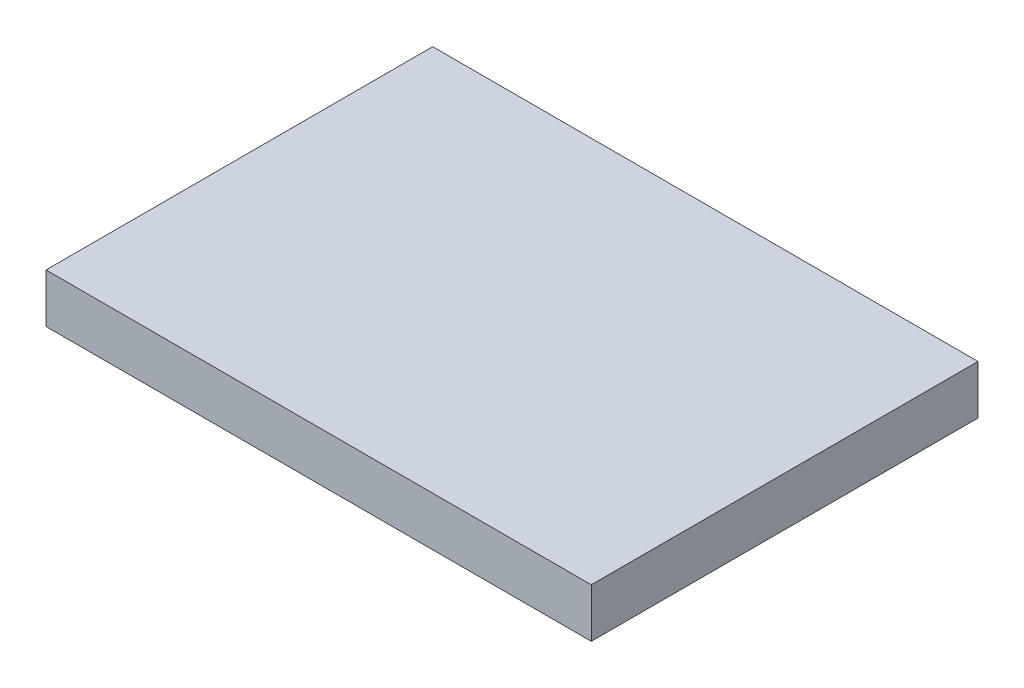
SolidWorks part; units mm, degrees
material "Plain Carbon Steel"
ref_plane "Front Plane" through (0, 0, 0) normal (0, 0, 1) x (1, 0, 0)
ref_plane "Top Plane" through (0, 0, 0) normal (0, 1, 0) x (1, 0, 0)
ref_plane "Right Plane" through (0, 0, 0) normal (1, 0, 0) x (0, 0, -1)
sketch "Sketch1" plane through (0, 0, 0) normal (0, 0, 1) x (1, 0, 0)
  line L1 (-39.6474, -7.3068) -> (2.6526, -7.3068)
  line L2 (-39.6474, -7.3068) -> (-39.6474, -11.1068)
  line L3 (-39.6474, -11.1068) -> (2.6526, -11.1068)
  line L4 (2.6526, -7.3068) -> (2.6526, -11.1068)
  dimension "D1" = 3.8
  dimension "D2" = 42.3
extrude "Boss-Extrude1" add sketch "Sketch1" along normal blind 30
